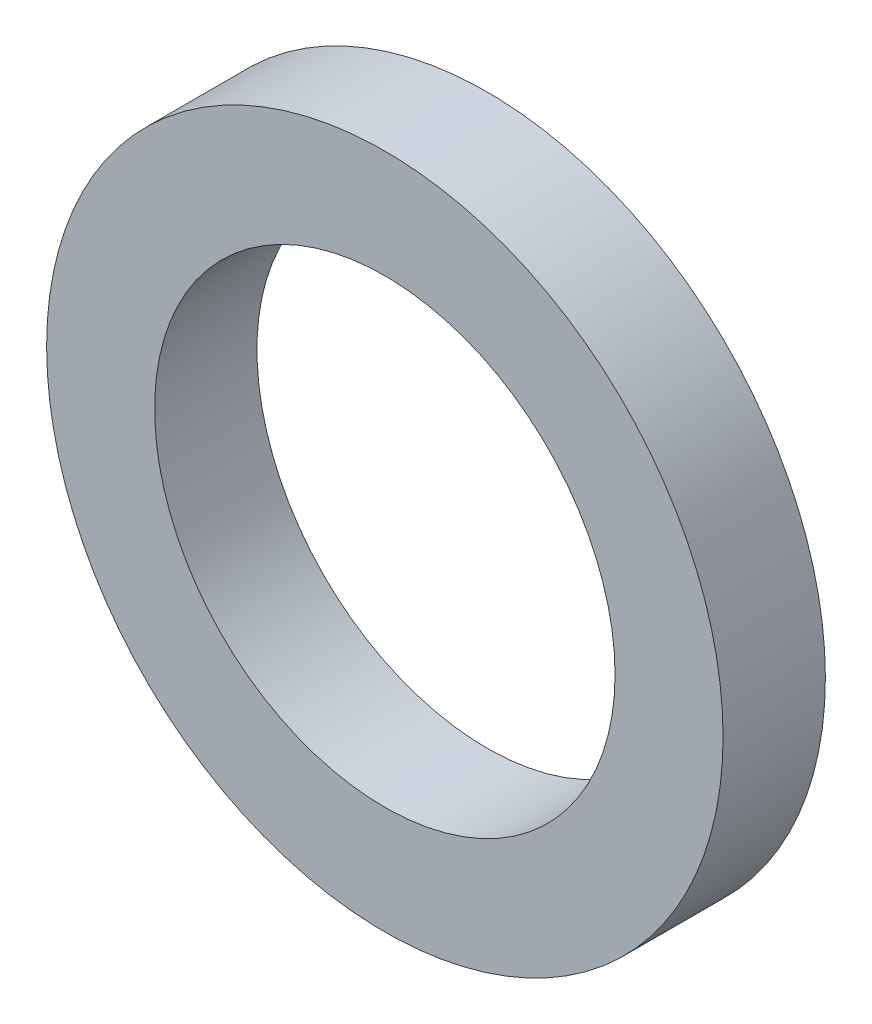
SolidWorks part; units mm, degrees
ref_plane "Front Plane" through (0, 0, 0) normal (1, 0, 0) x (0, 1, 0)
ref_plane "Top Plane" through (0, 0, 0) normal (0, 0, 1) x (0, 1, 0)
ref_plane "Right Plane" through (0, 0, 0) normal (0, 1, 0) x (-1, 0, 0)
sketch "Sketch1" plane through (0, 0, 0) normal (0, 0, 1) x (0, 1, 0)
  circle A0 centre (0, 0) radius 188.9125
  circle A1 centre (0, 0) radius 128.5875
  dimension "D1" = 257.175
  dimension "D2" = 377.825
extrude "Boss-Extrude1" add sketch "Sketch1" along normal mid plane 57.15
chamfer "Chamfer1" [suppressed] distance 38.1 angle 45
sketch "Sketch2" [suppressed] plane through (0, 0, 28.575) normal (0, 0, 1) x (1, 0, 0)
  line L0 (-188.9125, 0) -> (0, 0)
  line L1 (0, 0) -> (0, 188.9125)
  circle A0 centre (0, 0) radius 188.9125 construction
split "Split1" [suppressed] bodies to split 101
